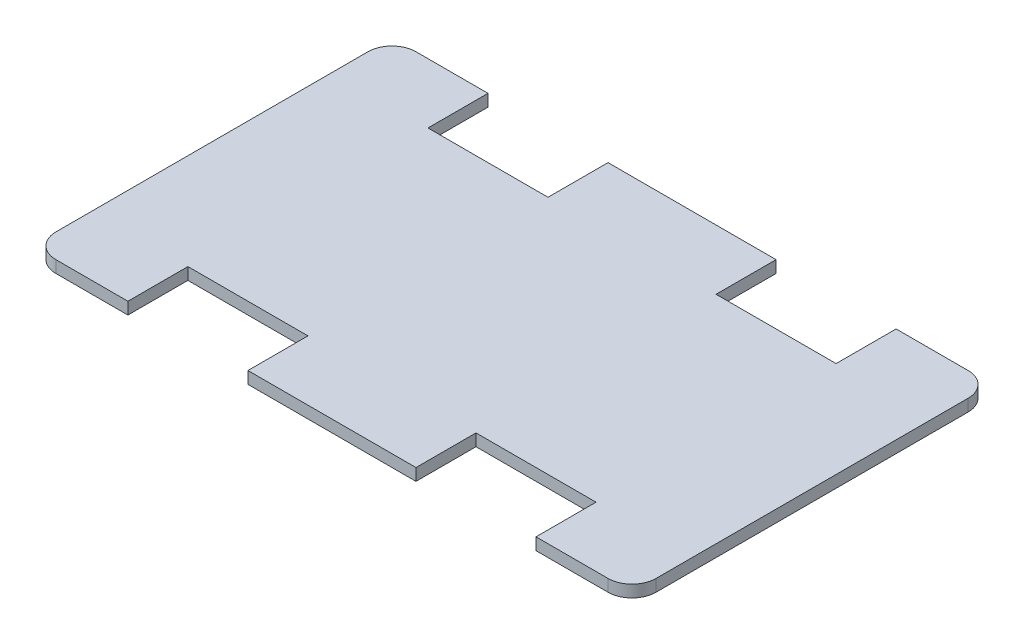
SolidWorks part; units mm, degrees
ref_plane "Front Plane" through (0, 0, 0) normal (0, 0, 1) x (1, 0, 0)
ref_plane "Top Plane" through (0, 0, 0) normal (0, 1, 0) x (1, 0, 0)
ref_plane "Right Plane" through (0, 0, 0) normal (1, 0, 0) x (0, 0, -1)
sketch "Sketch1" plane through (0, 0, 0) normal (0, 1, 0) x (1, 0, 0)
  line L0 (64.2704, 57.5107) -> (94.2704, 57.5107)
  line L1 (-135.7296, 57.5107) -> (-105.7296, 57.5107)
  line L2 (-145.7296, 47.5107) -> (-145.7296, -82.4893)
  line L3 (-135.7296, -92.4893) -> (-105.7296, -92.4893)
  line L4 (104.2704, 47.5107) -> (104.2704, -82.4893)
  line L6 (-105.7296, 57.5107) -> (-105.7296, 32.5107)
  line L7 (-105.7296, 32.5107) -> (-55.7296, 32.5107)
  line L8 (-55.7296, 57.5107) -> (-55.7296, 32.5107)
  line L10 (14.2704, 57.5107) -> (14.2704, 32.5107)
  line L11 (14.2704, 32.5107) -> (64.2704, 32.5107)
  line L12 (64.2704, 57.5107) -> (64.2704, 32.5107)
  line L13 (-105.7296, -67.4893) -> (-55.7296, -67.4893)
  line L14 (-105.7296, -67.4893) -> (-105.7296, -92.4893)
  line L16 (-55.7296, -67.4893) -> (-55.7296, -92.4893)
  line L17 (14.2704, -67.4893) -> (64.2704, -67.4893)
  line L18 (14.2704, -67.4893) -> (14.2704, -92.4893)
  line L20 (64.2704, -67.4893) -> (64.2704, -92.4893)
  line L21 (-55.7296, 57.5107) -> (14.2704, 57.5107)
  line L22 (-55.7296, -92.4893) -> (14.2704, -92.4893)
  line L23 (64.2704, -92.4893) -> (94.2704, -92.4893)
  arc A0 (94.2704, 57.5107) -> (104.2704, 47.5107) centre (94.2704, 47.5107) cw
  arc A1 (-145.7296, 47.5107) -> (-135.7296, 57.5107) centre (-135.7296, 47.5107) cw
  arc A2 (-145.7296, -82.4893) -> (-135.7296, -92.4893) centre (-135.7296, -82.4893) ccw
  arc A3 (94.2704, -92.4893) -> (104.2704, -82.4893) centre (94.2704, -82.4893) ccw
  point P24 (-145.7296, 57.5107)
  point P27 (-145.7296, -92.4893)
  point P30 (104.2704, -92.4893)
  dimension "D9" = 10
  dimension "D10" = 10
  dimension "D1" = 150
  dimension "D2" = 250
  dimension "D3" = 50
  dimension "D4" = 25
  dimension "D5" = 40
  dimension "D6" = 40
  dimension "D7" = 40
  dimension "D8" = 40
extrude "Boss-Extrude1" add sketch "Sketch1" along normal blind 5
